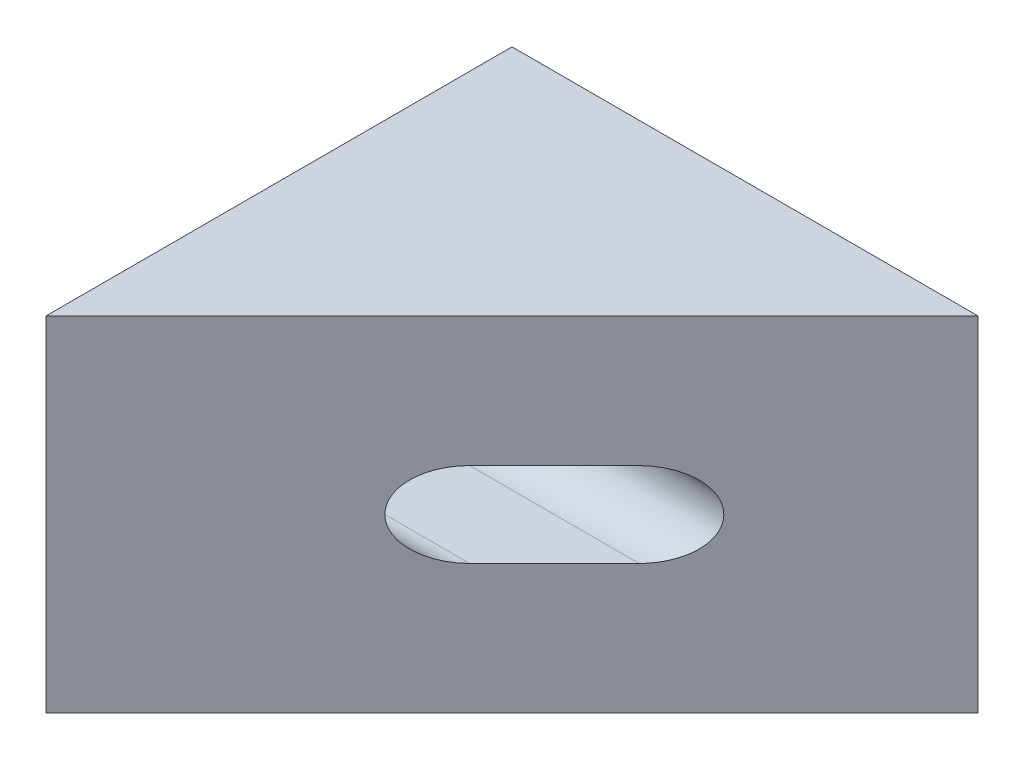
SolidWorks part; units mm, degrees
material "AISI 304"
ref_plane "前视基准面" through (0, 0, 0) normal (0, 0, 1) x (1, 0, 0)
ref_plane "上视基准面" through (0, 0, 0) normal (0, 1, 0) x (1, 0, 0)
ref_plane "右视基准面" through (0, 0, 0) normal (1, 0, 0) x (0, 0, -1)
sketch "Sketch1" plane through (0, 0, 0) normal (0, 1, 0) x (1, 0, 0)
  line L0 (0, 0) -> (0, -27.5)
  line L1 (0, -27.5) -> (27.5, 0)
  line L2 (27.5, 0) -> (0, 0)
  dimension "D1" = 27.5
extrude "Boss-Extrude1" add sketch "Sketch1" along normal mid plane 20.3
sketch "Sketch2" plane through (0, 0, 0) normal (-1, 0, 0) x (0, 0, 1)
  line L0 (0, 0) -> (32.6759, 0) construction
  line L1 (15, 0) -> (10, 0) construction
  line L2 (15, -2.5) -> (10, -2.5)
  line L3 (15, 2.5) -> (10, 2.5)
  line L4 (27.5, 10.15) -> (27.5, -10.15) construction
  arc A0 (15, -2.5) -> (15, 2.5) centre (15, 0) ccw
  arc A1 (10, 2.5) -> (10, -2.5) centre (10, 0) ccw
  point P5 (12.5, 0)
  point P12 (17.5, 0)
  dimension "D2" = 2.5
  dimension "D1" = 5
  dimension "D3" = 10
extrude "Cut-Extrude1" cut sketch "Sketch2" against normal blind 20.3
